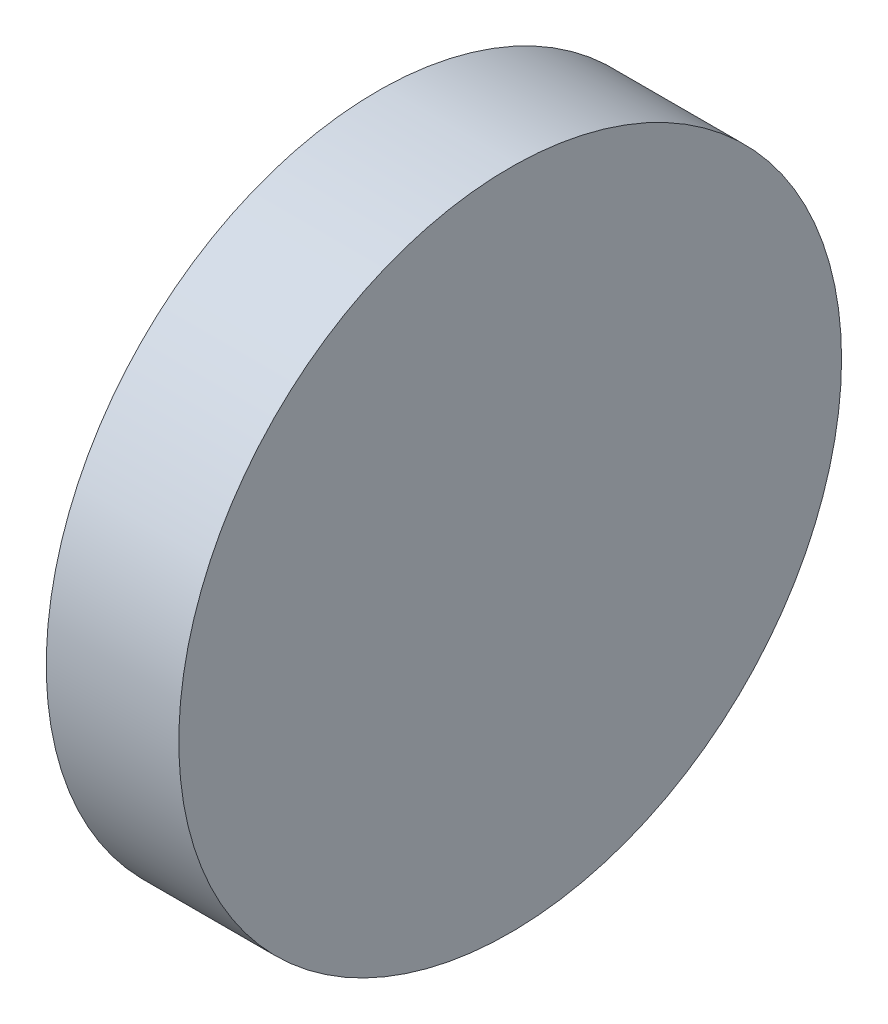
SolidWorks part; units mm, degrees
material "moto_pink"
ref_plane "Front Plane" through (0, 0, 0) normal (0, 0, 1) x (1, 0, 0)
ref_plane "Top Plane" through (0, 0, 0) normal (0, 1, 0) x (1, 0, 0)
ref_plane "Right Plane" through (0, 0, 0) normal (1, 0, 0) x (0, 0, -1)
sketch "Sketch1" plane through (0, 0, 0) normal (1, 0, 0) x (0, 0, -1)
  circle A0 centre (0, 0) radius 2.5
  dimension "D1" = 5
extrude "Boss-Extrude1" add sketch "Sketch1" along normal mid plane 1
